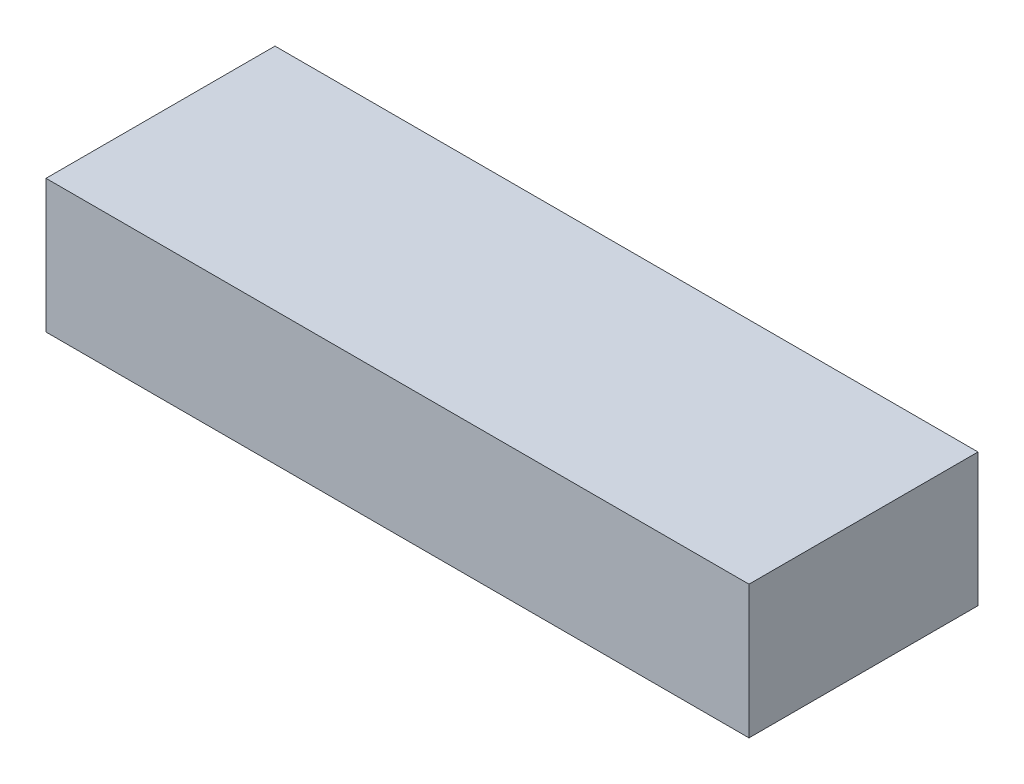
SolidWorks part; units mm, degrees
ref_plane "Front Plane" through (0, 0, 0) normal (0, 0, 1) x (1, 0, 0)
ref_plane "Top Plane" through (0, 0, 0) normal (0, 1, 0) x (1, 0, 0)
ref_plane "Right Plane" through (0, 0, 0) normal (1, 0, 0) x (0, 0, -1)
sketch "Sketch2" plane through (0, 0, 0) normal (0, 1, 0) x (1, 0, 0)
  line L1 (0, 0) -> (132, 0)
  line L2 (0, 0) -> (0, 43)
  line L3 (0, 43) -> (132, 43)
  line L4 (132, 0) -> (132, 43)
  dimension "D1" = 132
  dimension "D2" = 43
extrude "Boss-Extrude1" add sketch "Sketch2" along normal blind 25
